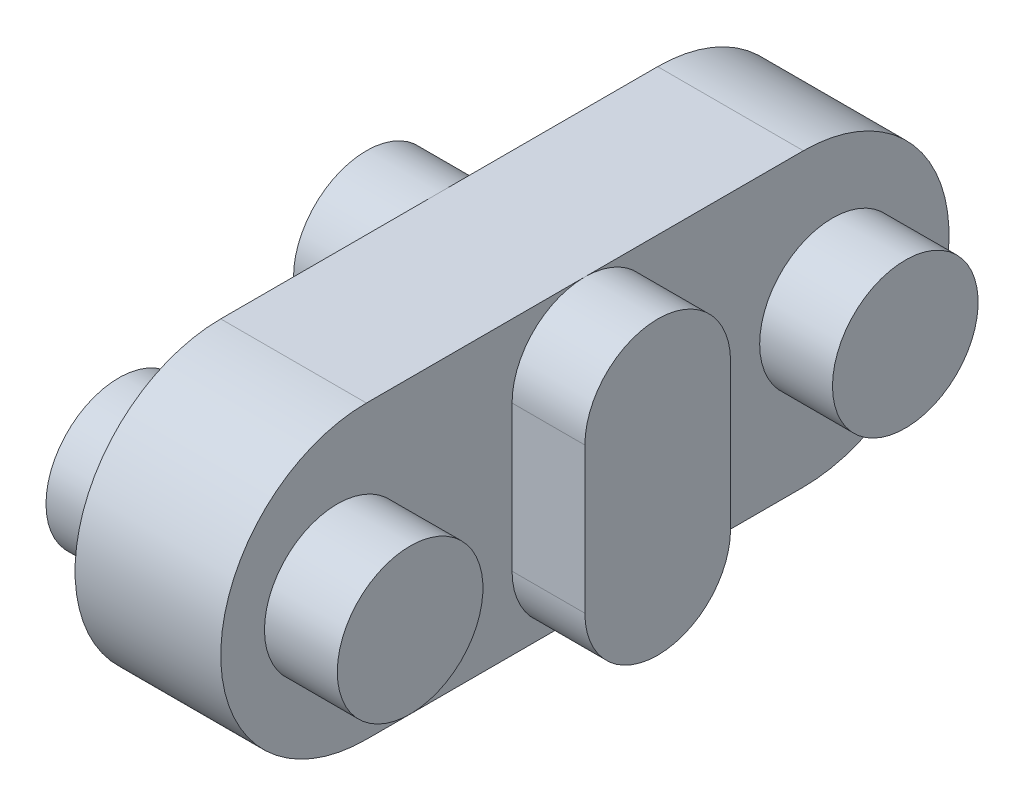
SolidWorks part; units mm, degrees
ref_plane "Front Plane" through (0, 0, 0) normal (0, 0, 1) x (1, 0, 0)
ref_plane "Top Plane" through (0, 0, 0) normal (0, 1, 0) x (1, 0, 0)
ref_plane "Right Plane" through (0, 0, 0) normal (1, 0, 0) x (0, 0, -1)
ref_plane "Plane1" through (5.0023, 0, 0) normal (1, 0, 0) x (0, 0, -1)
sketch "Sketch1" plane through (5.0023, 0, 0) normal (1, 0, 0) x (0, 0, -1)
  line L0 (-5, 0) -> (-20, 0)
  line L1 (-20, -10) -> (-5, -10)
  arc A0 (-20, 0) -> (-20, -10) centre (-20, -5) ccw
  arc A1 (-5, -10) -> (-5, 0) centre (-5, -5) ccw
extrude "Boss-Extrude1" add sketch "Sketch1" against normal blind 5.0023
ref_plane "Plane2" through (7.5023, 0, 0) normal (1, 0, 0) x (0, 0, -1)
sketch "Sketch2" plane through (7.5023, 0, 0) normal (1, 0, 0) x (0, 0, -1)
  line L0 (-15, -2.5) -> (-15, -7.5)
  line L1 (-10, -7.5) -> (-10, -2.5)
  arc A0 (-10, -2.5) -> (-15, -2.5) centre (-12.5, -2.5) ccw
  arc A1 (-15, -7.5) -> (-10, -7.5) centre (-12.5, -7.5) ccw
extrude "Boss-Extrude2" add sketch "Sketch2" against normal up to next
ref_plane "Plane3" through (-2.5, 0, 0) normal (-1, 0, 0) x (0, -1, 0)
sketch "Sketch3" plane through (-2.5, 0, 0) normal (-1, 0, 0) x (0, -1, 0)
  line L0 (7.5, 15) -> (2.5, 15)
  line L1 (2.5, 10) -> (7.5, 10)
  arc A0 (2.5, 15) -> (2.5, 10) centre (2.5, 12.5) ccw
  arc A1 (7.5, 10) -> (7.5, 15) centre (7.5, 12.5) ccw
extrude "Boss-Extrude3" add sketch "Sketch3" against normal up to next
ref_plane "Plane4" through (0, 0, 4) normal (0, 0, -1) x (-1, 0, 0)
sketch "Sketch4" plane through (0, 0, 4) normal (0, 0, -1) x (-1, 0, 0)
  line L0 (0, -2.5) -> (0, -5)
  line L1 (0, -5) -> (2.4977, -5)
  line L2 (2.4977, -5) -> (2.4977, -2.5)
  line L3 (2.4977, -2.5) -> (0, -2.5)
  line L4 (0, -5) -> (2.4977, -5) construction
revolve "Revolve1" add sketch "Sketch4" angle 360 about L4
sketch "Sketch5" plane through (0, 0, 4) normal (0, 0, -1) x (-1, 0, 0)
  line L0 (-7.5023, -2.5) -> (-7.5023, -5)
  line L1 (-7.5023, -5) -> (-5.0023, -5)
  line L2 (-5.0023, -5) -> (-5.0023, -2.5)
  line L3 (-5.0023, -2.5) -> (-7.5023, -2.5)
  line L4 (-7.5023, -5) -> (-5.0023, -5) construction
revolve "Revolve2" add sketch "Sketch5" angle 360 about L4
ref_plane "Plane5" through (0, 0, 21) normal (0, 0, -1) x (-1, 0, 0)
sketch "Sketch6" plane through (0, 0, 21) normal (0, 0, -1) x (-1, 0, 0)
  line L0 (-7.5023, -2.5) -> (-7.5023, -5)
  line L1 (-7.5023, -5) -> (-5.0023, -5)
  line L2 (-5.0023, -5) -> (-5.0023, -2.5)
  line L3 (-5.0023, -2.5) -> (-7.5023, -2.5)
  line L4 (-7.5023, -5) -> (-5.0023, -5) construction
revolve "Revolve3" add sketch "Sketch6" angle 360 about L4
sketch "Sketch7" plane through (0, 0, 21) normal (0, 0, -1) x (-1, 0, 0)
  line L0 (0, -2.5) -> (0, -5)
  line L1 (0, -5) -> (2.4977, -5)
  line L2 (2.4977, -5) -> (2.4977, -2.5)
  line L3 (2.4977, -2.5) -> (0, -2.5)
  line L4 (0, -5) -> (2.4977, -5) construction
revolve "Revolve4" add sketch "Sketch7" angle 360 about L4
